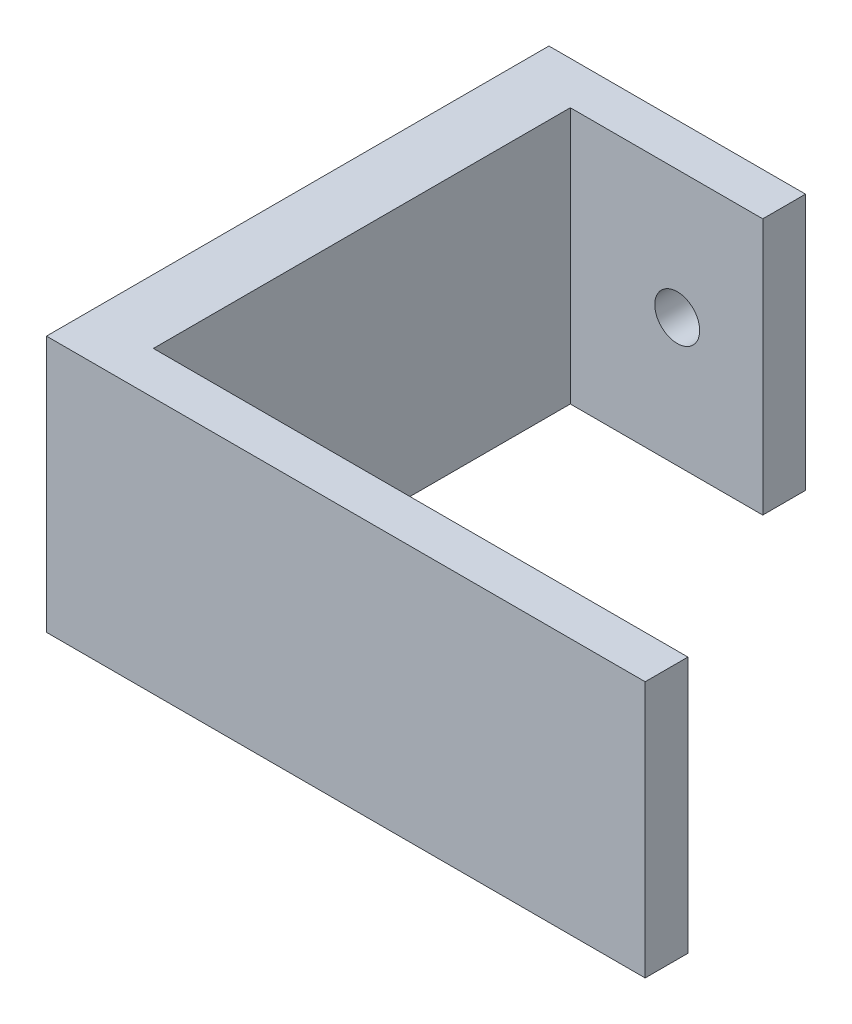
SolidWorks part; units mm, degrees
ref_plane "Front Plane" through (0, 0, 0) normal (0, 0, 1) x (1, 0, 0)
ref_plane "Top Plane" through (0, 0, 0) normal (0, 1, 0) x (1, 0, 0)
ref_plane "Right Plane" through (0, 0, 0) normal (1, 0, 0) x (0, 0, -1)
sketch "Sketch1" plane through (0, 0, 0) normal (0, 0, 1) x (1, 0, 0)
  line L1 (-44, -26) -> (-32, -26)
  line L2 (-44, -26) -> (-44, -14)
  line L3 (-44, -14) -> (-32, -14)
  line L4 (-32, -26) -> (-32, -14)
  circle A0 centre (-36, -20) radius 1.05
extrude "Link_Eye_Shelf" add sketch "Sketch1" along normal blind 2 from offset 23.5
sketch "Sketch2" plane through (0, 0, 0) normal (0, 0, 1) x (1, 0, 0)
  line L1 (-44, -26) -> (-41, -26)
  line L2 (-44, -26) -> (-44, -14)
  line L3 (-44, -14) -> (-41, -14)
  line L4 (-41, -26) -> (-41, -14)
extrude "Outboard_Web" add sketch "Sketch2" along normal blind 21.5 from offset 22.5
sketch "Sketch3" plane through (0, 0, 0) normal (0, 0, 1) x (1, 0, 0)
  line L1 (-44, -26) -> (-16, -26)
  line L2 (-44, -26) -> (-44, -14)
  line L3 (-44, -14) -> (-16, -14)
  line L4 (-16, -26) -> (-16, -14)
extrude "Carriage_Plate_Foot" add sketch "Sketch3" along normal blind 2 from offset 2
